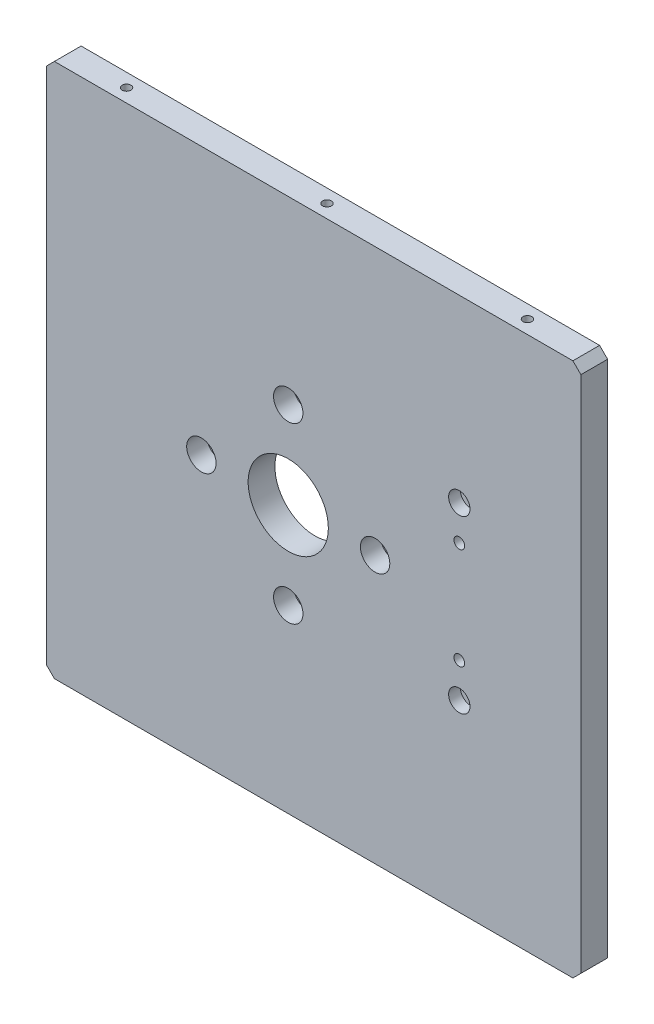
SolidWorks part; units mm, degrees
ref_plane "Plan de face" through (0, 0, 0) normal (0, 0, 1) x (1, 0, 0)
ref_plane "Plan de dessus" through (0, 0, 0) normal (0, 1, 0) x (1, 0, 0)
ref_plane "Plan de droite" through (0, 0, 0) normal (1, 0, 0) x (0, 0, -1)
sketch "Esquisse1" plane through (0, 0, 0) normal (0, 0, 1) x (1, 0, 0)
  line L1 (100, 100) -> (-100, 100)
  line L2 (100, 100) -> (100, -100)
  line L3 (100, -100) -> (-100, -100)
  line L4 (-100, 100) -> (-100, -100)
  line L5 (100, 100) -> (-100, -100) construction
  line L6 (100, -100) -> (-100, 100) construction
  point P0 (0, 0)
  dimension "D1" = 200
  dimension "D2" = 200
extrude "Boss.-Extru.1" add sketch "Esquisse1" along normal blind 10
sketch "Esquisse2" plane through (0, 0, 10) normal (0, 0, 1) x (1, 0, 0)
  line L0 (-100, 100) -> (-100, -100) construction
  line L1 (-100, -100) -> (100, -100) construction
  circle A0 centre (-9.5, 0) radius 15
  dimension "D1" = 30
  dimension "D2" = 90.5
  dimension "D3" = 100
extrude "Enlèv. mat.-Extru.1" cut sketch "Esquisse2" against normal through all
chamfer "Chanfrein1" distance 3 angle 45 4 edges at (100, 100, 5) (100, -100, 5) (-100, 100, 5) (-100, -100, 5)
hole_wizard "Dégagement M81" [suppressed] positions "Esquisse4" profile "Esquisse3" hole size "M8" standard "ISO"
sketch "Esquisse4" plane through (0, 0, 0) normal (0, 0, -1) x (-1, 0, 0)
  point P0 (-80, 80)
  point P3 (80, 80)
  point P6 (80, -80)
  point P9 (-80, -80)
sketch "Esquisse3" plane through (80, 80, 0) normal (1, 0, 0) x (0, 1, 0)
  line L0 (0, 0) -> (0, 10)
  line L1 (0, 10) -> (4.5, 10)
  line L2 (4.5, 10) -> (4.5, 0)
  line L5 (4.5, 0) -> (0, 0)
  line L11 (0, -6.35) -> (0, 107.95) construction
  dimension "Diamètre du perçage jusqu'au prochain" = 9
  dimension "Profondeur du perçage jusqu'au prochain" = 10
sketch "Esquisse5" plane through (0, 0, 10) normal (0, 0, 1) x (1, 0, 0)
  point P0 (54.5, 32.7)
  point P1 (54.5, 19.7)
  point P2 (54.5, -18.3)
  point P3 (54.5, -31.3)
hole_wizard "Chambrage pour vis à tête hexagonale M41" positions "Esquisse3D1" profile "Esquisse6" counterbore size "M4" standard "ISO" end condition through all
sketch3d "Esquisse3D1"
  point P0 (54.5, 32.7, 10)
  point P3 (54.5, -31.3, 10)
sketch "Esquisse6" plane through (54.5, 32.7, 10) normal (1, 0, 0) x (0, -1, 0)
  line L0 (0, 0) -> (0, 10)
  line L1 (0, 10) -> (2.25, 10)
  line L3 (2.25, 10) -> (2.25, 4.4)
  line L4 (2.25, 4.4) -> (4, 4.4)
  line L5 (4, 4.4) -> (4, 0)
  line L7 (4, 0) -> (0, 0)
  line L11 (0, -6.35) -> (0, 107.95) construction
  dimension "Diamètre du perçage jusqu'au prochain" = 4.5
  dimension "Profondeur du perçage jusqu'au prochain" = 10
  dimension "Diamètre du chambrage" = 8
  dimension "Profondeur du chambrage" = 4.4
hole_wizard "Trous de centrage Ø4.0mmClearance 1" positions "Esquisse3D2" profile "Esquisse7" hole size "Ø4.0" standard "ISO" end condition through all
sketch3d "Esquisse3D2"
  point P0 (54.5, -18.3, 10)
  point P3 (54.5, 19.7, 10)
sketch "Esquisse7" plane through (54.5, -18.3, 10) normal (1, 0, 0) x (0, -1, 0)
  line L0 (0, 0) -> (0, 10)
  line L1 (0, 10) -> (2, 10)
  line L2 (2, 10) -> (2, 0)
  line L5 (2, 0) -> (0, 0)
  line L11 (0, -6.35) -> (0, 107.95) construction
  dimension "Diamètre du perçage jusqu'au prochain" = 4
  dimension "Profondeur du perçage jusqu'au prochain" = 10
hole_wizard "Trou taraudé M61" [suppressed] positions "Esquisse9" profile "Esquisse8" tap size "M6" standard "ISO"
sketch "Esquisse9" plane through (0, 0, 10) normal (0, 0, 1) x (1, 0, 0)
  point P0 (-26.4817, -24.7134)
  point P2 (17.4647, 12.9981)
  point P4 (-7.2751, 29.967)
sketch "Esquisse8" plane through (-26.4817, -24.7134, 10) normal (1, 0, 0) x (0, -1, 0)
  line L0 (0, 0) -> (0, 10)
  line L1 (0, 10) -> (2.5, 10)
  line L2 (2.5, 10) -> (2.5, 0)
  line L5 (2.5, 0) -> (0, 0)
  line L11 (0, -6.35) -> (0, 107.95) construction
  dimension "Diamètre du trou pour taraudage jusqu'au prochain" = 5
  dimension "Profondeur du trou pour taraudage jusqu'au prochain" = 10
cosmetic thread "Filetage de perçage1" [suppressed] parameters "D2"=6
cosmetic thread "Filetage de perçage2" [suppressed] parameters "D2"=6
cosmetic thread "Filetage de perçage3" [suppressed] parameters "D2"=6
hole_wizard "Trous de centrage Ø8.0mm1" [suppressed] positions "Esquisse11" profile "Esquisse10" hole size "Ø8.0" standard "ISO"
sketch "Esquisse11" [suppressed] plane through (0, 0, 10) normal (0, 0, 1) x (1, 0, 0)
  line L0 (80, -63) -> (80, -80) construction
  line L5 (80, 80) -> (80, 63) construction
  line L7 (-80, 80) -> (-80, 63) construction
  line L9 (-80, -63) -> (-80, -80) construction
  point P0 (80, -63)
  point P6 (80, 63)
  point P8 (-80, 63)
  point P10 (-80, -63)
  dimension "D1" = 17
  dimension "D2" = 17
  dimension "D3" = 17
  dimension "D4" = 17
sketch "Esquisse10" plane through (80, -63, 10) normal (1, 0, 0) x (0, -1, 0)
  line L0 (0, 0) -> (0, 10)
  line L1 (0, 10) -> (4, 10)
  line L2 (4, 10) -> (4, 0)
  line L5 (4, 0) -> (0, 0)
  line L11 (0, -6.35) -> (0, 107.95) construction
  dimension "Diamètre du perçage jusqu'au prochain" = 8
  dimension "Profondeur du perçage jusqu'au prochain" = 10
hole_wizard "Trou taraudé M51" [suppressed] positions "Esquisse13" profile "Esquisse12" tap size "M5" standard "ISO"
sketch "Esquisse13" plane through (0, 0, 10) normal (0, 0, 1) x (1, 0, 0)
  point P0 (13.5, 7.0855)
  point P2 (13.5, -12.9145)
sketch "Esquisse12" plane through (13.5, 7.0855, 10) normal (1, 0, 0) x (0, -1, 0)
  line L0 (0, 0) -> (0, 10)
  line L1 (0, 10) -> (2.1, 10)
  line L2 (2.1, 10) -> (2.1, 0)
  line L5 (2.1, 0) -> (0, 0)
  line L11 (0, -6.35) -> (0, 107.95) construction
  dimension "Diamètre du trou pour taraudage jusqu'au prochain" = 4.2
  dimension "Profondeur du trou pour taraudage jusqu'au prochain" = 10
cosmetic thread "Filetage de perçage4" [suppressed] parameters "D2"=5
cosmetic thread "Filetage de perçage5" [suppressed] parameters "D2"=5
hole_wizard "Chambrage pour vis à tête hexagonale M61" positions "Esquisse15" profile "Esquisse14" counterbore size "M6" standard "ISO" end condition through all
sketch "Esquisse15" plane through (0, 0, 10) normal (0, 0, 1) x (1, 0, 0)
  point P0 (23, 0)
  point P2 (-9.5, 32.5)
  point P4 (-42, 0)
  point P6 (-9.5, -32.5)
sketch "Esquisse14" plane through (23, 0, 10) normal (1, 0, 0) x (0, -1, 0)
  line L0 (0, 0) -> (0, 10)
  line L1 (0, 10) -> (3.3, 10)
  line L3 (3.3, 10) -> (3.3, 7.4)
  line L4 (3.3, 7.4) -> (5.5, 7.4)
  line L5 (5.5, 7.4) -> (5.5, 0)
  line L7 (5.5, 0) -> (0, 0)
  line L11 (0, -6.35) -> (0, 107.95) construction
  dimension "Diamètre du perçage jusqu'au prochain" = 6.6
  dimension "Profondeur du perçage jusqu'au prochain" = 10
  dimension "Diamètre du chambrage" = 11
  dimension "Profondeur du chambrage" = 7.4
hole_wizard "Trou taraudé M41" positions "Esquisse17" profile "Esquisse18" tap size "M4" standard "ISO"
sketch "Esquisse17" plane through (0, 100, 0) normal (0, 1, 0) x (1, 0, 0)
  line L0 (-111.7688, -5) -> (122.0395, -5) construction
  line L2 (0, 30.3431) -> (0, -44.975) construction
  line L4 (97, 0) -> (-97, 0) construction
  line L5 (97, -10) -> (-97, -10) construction
  point P0 (-75, -5)
  point P2 (0, -5)
  point P4 (75, -5)
  dimension "D1" = 150
sketch "Esquisse18" plane through (-75, 100, 5) normal (1, 0, 0) x (0, 0, 1)
  line L0 (0, 0) -> (0, 14.9914)
  line L1 (0, 14.9914) -> (1.65, 14)
  line L2 (1.65, 14) -> (1.65, 0)
  line L5 (1.65, 0) -> (0, 0)
  line L10 (0, 14.9914) -> (-1.65, 14) construction
  line L11 (0, -6.35) -> (0, 107.95) construction
  dimension "Diamètre du trou pour taraudage" = 3.3
  dimension "Profondeur du trou pour taraudage" = 14
  dimension "Angle de pointe" = 118
cosmetic thread "Filetage de perçage6" parameters "D1"=13, "D2"=4
cosmetic thread "Filetage de perçage7" parameters "D1"=13, "D2"=4
cosmetic thread "Filetage de perçage8" parameters "D1"=13, "D2"=4
hole_wizard "Trou taraudé M42" positions "Esquisse21" profile "Esquisse20" tap size "M4" standard "ISO"
sketch "Esquisse21" plane through (0, -100, 0) normal (0, -1, 0) x (-1, 0, 0)
  line L0 (111.5674, -5) -> (-120.4284, -5) construction
  line L2 (0, -28.8642) -> (0, 40.6138) construction
  line L4 (97, -10) -> (-97, -10) construction
  line L5 (97, 0) -> (-97, 0) construction
  point P0 (75, -5)
  point P2 (0, -5)
  point P4 (-75, -5)
  dimension "D1" = 150
sketch "Esquisse20" plane through (-75, -100, 5) normal (1, 0, 0) x (0, 0, -1)
  line L0 (0, 0) -> (0, 14.9914)
  line L1 (0, 14.9914) -> (1.65, 14)
  line L2 (1.65, 14) -> (1.65, 0)
  line L5 (1.65, 0) -> (0, 0)
  line L10 (0, 14.9914) -> (-1.65, 14) construction
  line L11 (0, -6.35) -> (0, 107.95) construction
  dimension "Diamètre du trou pour taraudage" = 3.3
  dimension "Profondeur du trou pour taraudage" = 14
  dimension "Angle de pointe" = 118
cosmetic thread "Filetage de perçage9" parameters "D1"=13, "D2"=4
cosmetic thread "Filetage de perçage10" parameters "D1"=13, "D2"=4
cosmetic thread "Filetage de perçage11" parameters "D1"=13, "D2"=4
hole_wizard "Trou taraudé M52" positions "Esquisse23" profile "Esquisse22" tap size "M5" standard "ISO"
sketch "Esquisse23" plane through (-100, 0, 0) normal (-1, 0, 0) x (0, 0, 1)
  point P0 (5, 0)
  point P2 (5, -75)
  point P4 (5, 75)
sketch "Esquisse22" plane through (-100, 0, 5) normal (0, 1, 0) x (0, 0, 1)
  line L0 (0, 0) -> (0, 15)
  line L1 (0, 15) -> (2.1, 15)
  line L2 (2.1, 15) -> (2.1, 0)
  line L5 (2.1, 0) -> (0, 0)
  line L10 (0, 15) -> (-2.1, 15) construction
  line L11 (0, -6.35) -> (0, 107.95) construction
  dimension "Diamètre du trou pour taraudage" = 4.2
  dimension "Profondeur du trou pour taraudage" = 15
  dimension "Angle de pointe" = 180
